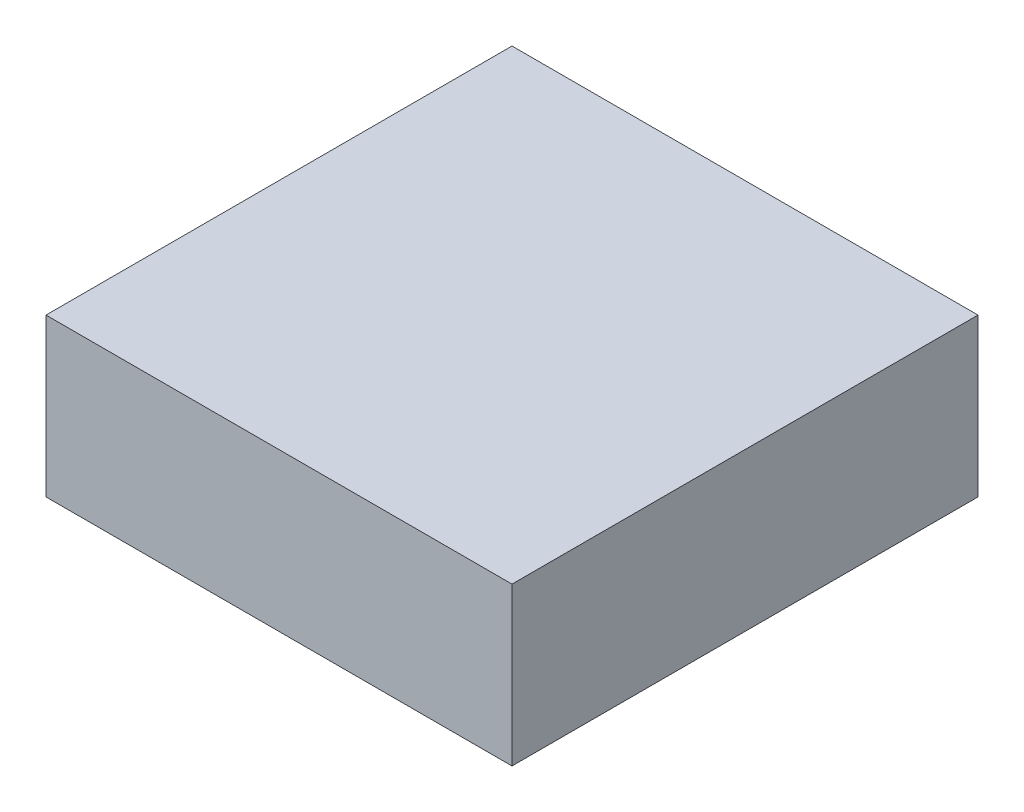
SolidWorks part; units mm, degrees
ref_plane "Front Plane" through (0, 0, 0) normal (0, 0, 1) x (1, 0, 0)
ref_plane "Top Plane" through (0, 0, 0) normal (0, 1, 0) x (1, 0, 0)
ref_plane "Right Plane" through (0, 0, 0) normal (1, 0, 0) x (0, 0, -1)
sketch "Sketch2" plane through (0, 0, 0) normal (0, 1, 0) x (1, 0, 0)
  line L1 (-9.017, -9.017) -> (9.017, -9.017)
  line L2 (-9.017, -9.017) -> (-9.017, 9.017)
  line L3 (-9.017, 9.017) -> (9.017, 9.017)
  line L4 (9.017, -9.017) -> (9.017, 9.017)
  line L5 (-9.017, -9.017) -> (9.017, 9.017) construction
  line L6 (-9.017, 9.017) -> (9.017, -9.017) construction
  point P0 (0, 0)
  dimension "D1" = 18.034
  dimension "D2" = 18.034
extrude "Boss-Extrude1" add sketch "Sketch2" along normal blind 6.096 contours L2 L1 L4 L3
